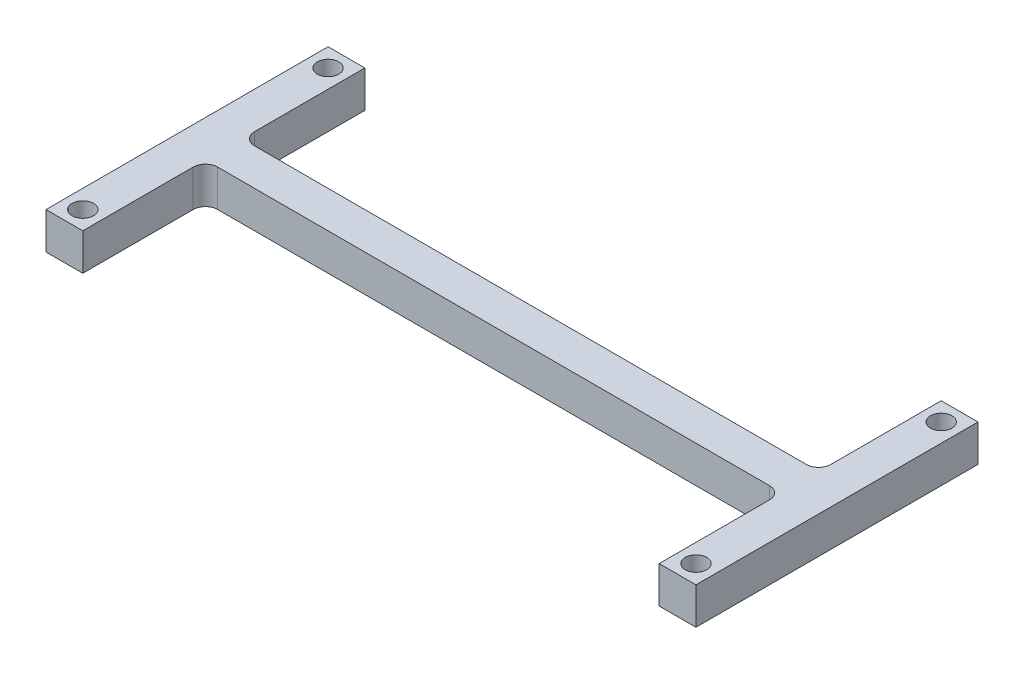
SolidWorks part; units mm, degrees
ref_plane "Front Plane" through (0, 0, 0) normal (0, 0, 1) x (1, 0, 0)
ref_plane "Top Plane" through (0, 0, 0) normal (0, 1, 0) x (1, 0, 0)
ref_plane "Right Plane" through (0, 0, 0) normal (1, 0, 0) x (0, 0, -1)
sketch "Sketch1" plane through (0, 0, 0) normal (0, 1, 0) x (1, 0, 0)
  line L1 (-53, -3) -> (53, -3)
  line L2 (-53, -3) -> (-53, 3)
  line L3 (-53, 3) -> (53, 3)
  line L4 (53, -3) -> (53, 3)
  line L5 (-53, -3) -> (53, 3) construction
  line L6 (-53, 3) -> (53, -3) construction
  point P0 (0, 0)
  dimension "D1" = 106
  dimension "D2" = 6
extrude "Boss-Extrude1" add sketch "Sketch1" along normal blind 6
sketch "Sketch2" plane through (0, 6, 0) normal (0, 1, 0) x (1, 0, 0)
  line L0 (0, 9.7282) -> (0, -10.3061) construction
  line L1 (-53, 3) -> (-47, 3)
  line L2 (-53, 3) -> (-53, 23)
  line L3 (-53, 23) -> (-47, 23)
  line L4 (-47, 3) -> (-47, 23)
  line L5 (-12.2807, 0) -> (11.9917, 0) construction
  line L6 (-53, -23) -> (-47, -23)
  line L7 (-53, -3) -> (-53, -23)
  line L8 (-47, -3) -> (-47, -23)
  line L9 (-53, -3) -> (-47, -3)
  line L10 (53, -3) -> (47, -3)
  line L11 (47, -3) -> (47, -23)
  line L12 (53, -3) -> (53, -23)
  line L13 (53, -23) -> (47, -23)
  line L14 (47, 3) -> (47, 23)
  line L15 (53, 23) -> (47, 23)
  line L16 (53, 3) -> (53, 23)
  line L17 (53, 3) -> (47, 3)
  circle A0 centre (-50, 20) radius 1.75
  circle A1 centre (-50, -20) radius 1.75
  circle A2 centre (50, -20) radius 1.75
  circle A3 centre (50, 20) radius 1.75
  dimension "D2" = 3.5
  dimension "D1" = 20
  dimension "D3" = 20
  dimension "D4" = 50
  dimension "D5" = 6
extrude "Boss-Extrude2" add sketch "Sketch2" against normal blind 6
fillet "Fillet1" radius 2 4 edges at (-47, 3, 3) (47, 3, 3) (47, 3, -3) (-47, 3, -3)
